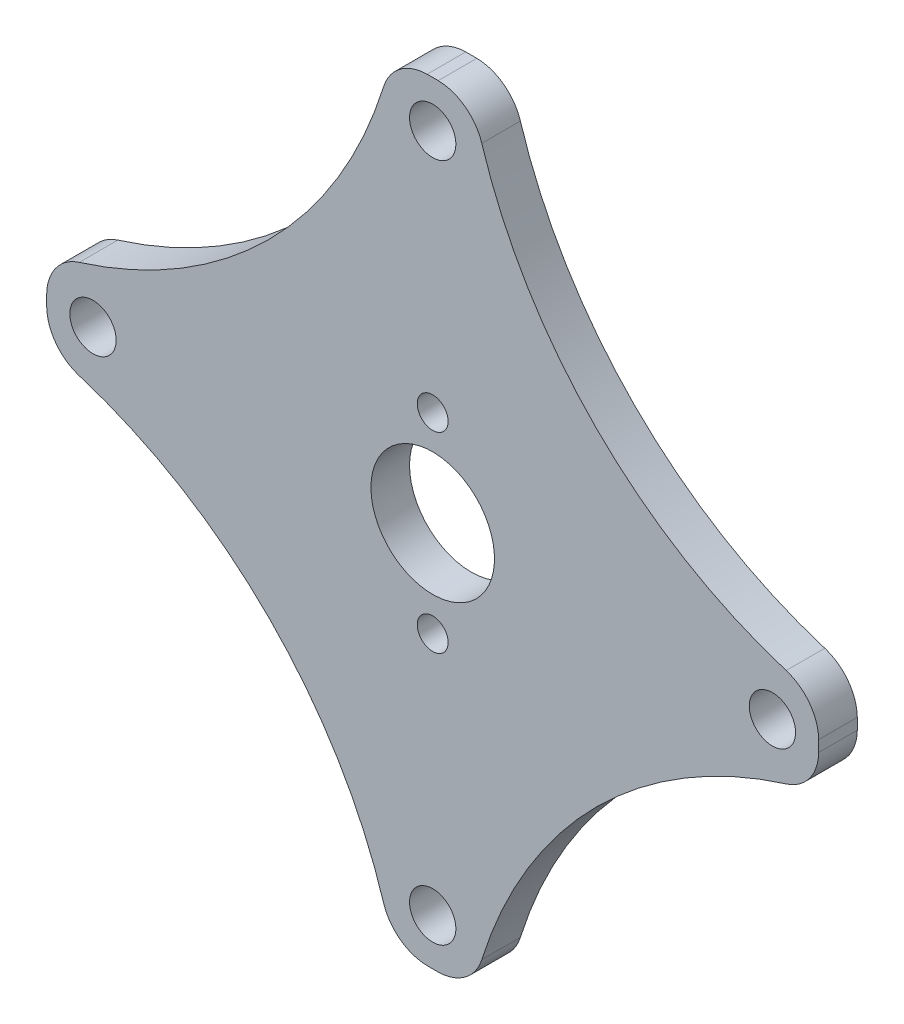
SolidWorks part; units mm, degrees
ref_plane "前视基准面" through (0, 0, 0) normal (0, 0, 1) x (1, 0, 0)
ref_plane "上视基准面" through (0, 0, 0) normal (0, 1, 0) x (1, 0, 0)
ref_plane "右视基准面" through (0, 0, 0) normal (1, 0, 0) x (0, 0, -1)
other "Configuration Table"
sketch "草图1" plane through (0, 0, 0) normal (0, 0, 1) x (1, 0, 0)
  line L0 (0, 0) -> (0, 22) construction
  line L1 (0, 0) -> (22, 0) construction
  circle A0 centre (0, 0) radius 22 construction
  circle A1 centre (0, 0) radius 16.5 construction
  circle A2 centre (0, 0) radius 25
  circle A3 centre (0, 22) radius 1.5
  circle A4 centre (22, 0) radius 1.5
  circle A5 centre (0, -22) radius 1.5
  circle A6 centre (-22, 0) radius 1.5
  dimension "D1" = 44
  dimension "D2" = 33
  dimension "D3" = 3
  dimension "D4" = 3
  dimension "D6" = 90
  dimension "D5" = 3
extrude "凸台-拉伸1" add sketch "草图1" along normal blind 2.5
sketch "草图3" plane through (0, 0, 0) normal (0, 0, -1) x (-1, 0, 0)
  line L0 (0, 0) -> (0, 22) construction
  circle A0 centre (0, 0) radius 10.5
  circle A1 centre (0, 0) radius 4
  circle A2 centre (0, 6.2) radius 1
  circle A3 centre (0, -6.2) radius 1
  dimension "D1" = 21
  dimension "D2" = 8
  dimension "D3" = 2
  dimension "D4" = 2
  dimension "D5" = 6.2
  dimension "D6" = 6.2
extrude "切除-拉伸2" cut sketch "草图3" against normal through all both and the other way through all contours A2 | A1 | A3
sketch "草图5" plane through (0, 0, 0) normal (0, 0, -1) x (-1, 0, 0)
  line L0 (-31.8198, 31.8198) -> (0, 0) construction
  line L1 (-22, 0) -> (0, 0) construction
  arc A0 (-24.8604, 2.6382) -> (-2.6382, 24.8604) centre (-31.8198, 31.8198) ccw
  circle A5 centre (0, 0) radius 25 construction
  arc A6 (2.6382, 24.8604) -> (24.8604, 2.6382) centre (31.8198, 31.8198) ccw
  circle A7 centre (0, 0) radius 25
  circle A8 centre (0, 0) radius 25
  arc A9 (24.8604, -2.6382) -> (2.6382, -24.8604) centre (31.8198, -31.8198) ccw
  arc A10 (-2.6382, -24.8604) -> (-24.8604, -2.6382) centre (-31.8198, -31.8198) ccw
  point P22 (0, 0)
  circle M3 centre (0, 0) radius 25
  dimension "D2" = 30
  dimension "D1" = 0
  dimension "D4" = 45
  dimension "D5" = 4
  dimension "D3" = 45
extrude "切除-拉伸5" cut sketch "草图5" against normal blind 10 contours A0 M3 | A8 A10 | A8 A9 | A6 M3
fillet "圆角2" radius 3 8 edges at (24.8604, 2.6382, 1.25) (2.6382, 24.8604, 1.25) (-2.6382, 24.8604, 1.25) (-24.8604, 2.6382, 1.25) (-24.8604, -2.6382, 1.25) (-2.6382, -24.8604, 1.25) (2.6382, -24.8604, 1.25) (24.8604, -2.6382, 1.25)
